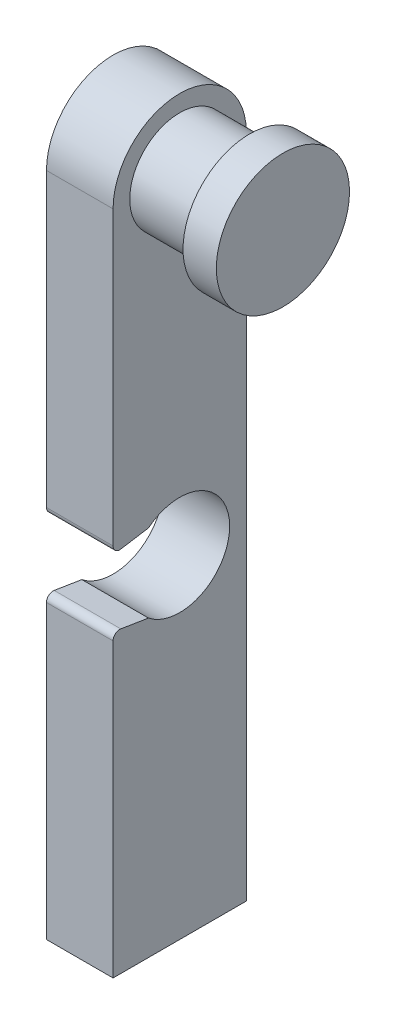
SolidWorks part; units mm, degrees
ref_plane "Plan de face" through (0, 0, 0) normal (0, 0, 1) x (1, 0, 0)
ref_plane "Plan de dessus" through (0, 0, 0) normal (0, 1, 0) x (1, 0, 0)
ref_plane "Plan de droite" through (0, 0, 0) normal (1, 0, 0) x (0, 0, -1)
sketch "Esquisse1" plane through (0, 0, 0) normal (1, 0, 0) x (0, 0, -1)
  line L0 (-13.6697, 68.3486) -> (-2, 10) construction
  line L2 (2, 10) -> (2, -10)
  line L3 (2, -10) -> (-2, -10)
  line L4 (-2, 10) -> (-2, -10)
  line L5 (2, 10) -> (13.6697, 68.3486) construction
  line L6 (2, -10) -> (0, 0) construction
  line L7 (0, 0) -> (-2, -10) construction
  arc A0 (2, 10) -> (-2, 10) centre (0, 10) ccw
  point P0 (0, 0)
  point P6 (0, 40)
  dimension "D1" = 4
  dimension "D2" = 20
extrude "BASE" add sketch "Esquisse1" along normal blind 2
sketch "Esquisse2" plane through (2, 0, 0) normal (1, 0, 0) x (0, 0, -1)
  line L0 (-2, 10) -> (2, 10) construction
  line L1 (2, 10) -> (0, 12) construction
  line L2 (0, 12) -> (0, 39.6014) construction
  arc A0 (2, 10) -> (-2, 10) centre (0, 10) ccw construction
  circle A1 centre (0, 10) radius 1.5
  dimension "D1" = 3
extrude "BOSS FIX" add sketch "Esquisse2" along normal blind 2.1
sketch "Esquisse3" plane through (4.1, 0, 0) normal (1, 0, 0) x (0, 0, -1)
  circle A0 centre (0, 10) radius 2
  dimension "D1" = 4
extrude "BOSS BLOCAGE" add sketch "Esquisse3" along normal blind 1
sketch "Esquisse4" plane through (0, 0, 0) normal (-1, 0, 0) x (0, 0, 1)
  line L2 (0, 2.5) -> (2, 2.5) construction
  line L4 (0, 5) -> (0, 2.5) construction
  line L5 (0, 2.5) -> (2, 2.5) construction
  line L6 (2, 2.5) -> (0, 5) construction
  line L7 (-2, 10) -> (2, 10) construction
  line L8 (0, 10) -> (0, 0) construction
  line L14 (0, 0) -> (2, -2.5) construction
  line L15 (2, 1) -> (0.937, 1.1713)
  line L16 (2, -1) -> (2, 1)
  line L17 (0.937, -1.1713) -> (2, -1)
  arc A1 (2, 10) -> (-2, 10) centre (0, 10) ccw construction
  arc A2 (0.937, -1.1713) -> (0.937, 1.1713) centre (0, 0) cw
  point P7 (0, 10)
  dimension "D3" = 2.5
extrude "VIDE TIGE" cut sketch "Esquisse4" against normal up to surface (2 mm away) up to face at (2, 0.5, 0)
fillet "CONGE TIGE" radius 0.2 2 edges at (1, -1, 2) (1, 1, 2)
